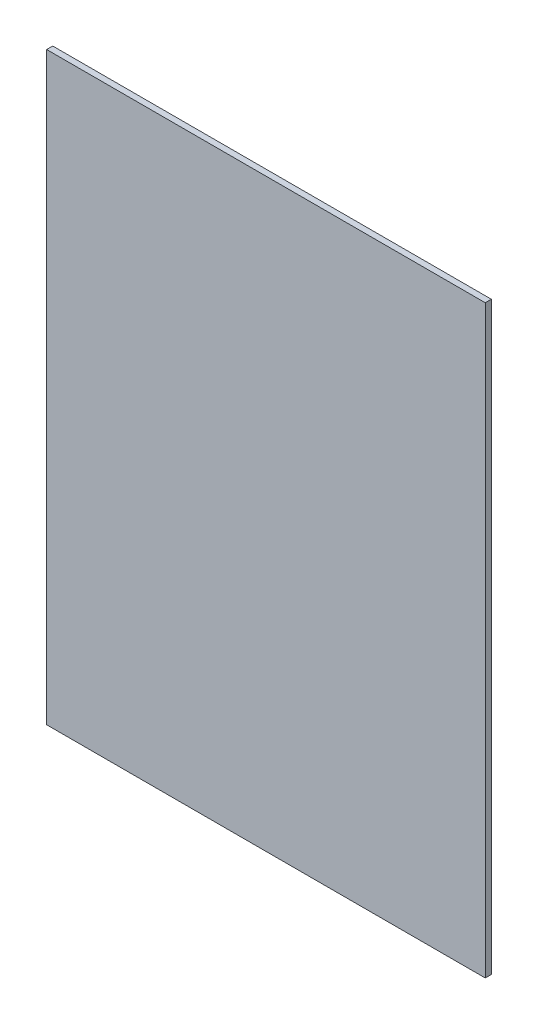
SolidWorks part; units mm, degrees
material "Pine"
ref_plane "Front Plane" through (0, 0, 0) normal (0, 0, 1) x (1, 0, 0)
ref_plane "Top Plane" through (0, 0, 0) normal (0, 1, 0) x (1, 0, 0)
ref_plane "Right Plane" through (0, 0, 0) normal (1, 0, 0) x (0, 0, -1)
sketch "Sketch1" plane through (0, 0, 0) normal (0, 0, 1) x (1, 0, 0)
  line L1 (0, 0) -> (1371.6, 0)
  line L2 (0, 0) -> (0, -1828.8)
  line L3 (0, -1828.8) -> (1371.6, -1828.8)
  line L4 (1371.6, 0) -> (1371.6, -1828.8)
  dimension "D1" = 1371.6
  dimension "D2" = 1828.8
extrude "Boss-Extrude1" add sketch "Sketch1" along normal blind 19.05
equation "\"TableFrontWidth\"=48"
equation "\"TableSideWidth\"=66"
equation "\"LegWidth\"=3.5"
equation "\"LegHeight\"=30"
equation "\"LegDistToBottomStretcher\"=7"
equation "\"BottomStretcherLength\"=\"TableFrontWidth\""
equation "\"SideStretcherLength\"=\"TableSideWidth\"-3"
equation "\"BottomSupportLength\"=\"TableSideWidth\"-3"
equation "\"BottomPlywoodFrontDim\"=\"TableFrontWidth\"-\"LegWidth\"*2-3"
equation "\"BottomPlywoodSideDim\"=\"BottomSupportLength\""
equation "\"D2@Sketch1\"=\"TableSideWidth\"+\"OverhangSideDim\"+\"OverhangSideDim\""
equation "\"D1@Sketch1\"=\"TableFrontWidth\"+\"OverhangFrontDim\"+\"OverhangFrontDim\""
equation "\"TotalBottomSupports\"=4"
equation "\"TotalBottomSupportsLessOne\"=\"TotalBottomSupports\"-1"
equation "\"TotalTopSupports\"=5"
equation "\"TotalTopSupportsLessOne\"=\"TotalTopSupports\"-1"
equation "\"TopSupportSpread\"=\"TableFrontWidth\"-1.5"
equation "\"DistBetweenTopSupports\"=\"TopSupportSpread\"/\"TotalTopSupportsLessOne\""
equation "\"BottomSupportSpread\"= \"BottomPlywoodFrontDim\" - 1.5"
equation "\"DistBetweenBottomSupports\"=\"BottomSupportSpread\"/\"TotalBottomSupportsLessOne\""
equation "\"OverhangFrontDim\"=3"
equation "\"OverhangSideDim\"=3"
